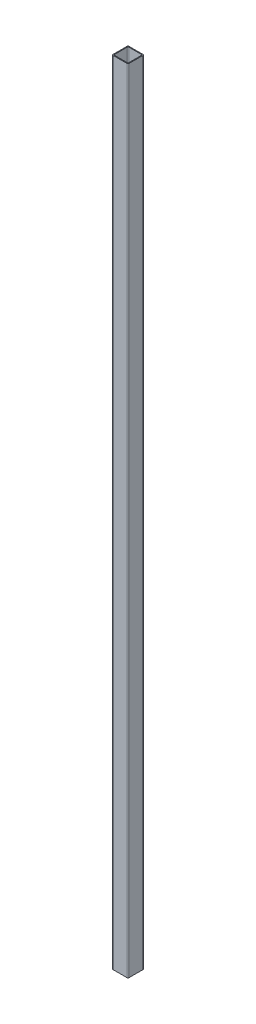
SolidWorks part; units mm, degrees
ref_plane "Спереди" through (0, 0, 0) normal (0, 0, 1) x (1, 0, 0)
ref_plane "Сверху" through (0, 0, 0) normal (0, 1, 0) x (1, 0, 0)
ref_plane "Справа" through (0, 0, 0) normal (1, 0, 0) x (0, 0, -1)
sketch "Эскиз2" plane through (0, 0, 0) normal (0, 1, 0) x (1, 0, 0)
  line L1 (-18, 20) -> (18, 20)
  line L2 (-20, 18) -> (-20, -18)
  line L3 (-18, -20) -> (18, -20)
  line L4 (20, 18) -> (20, -18)
  line L5 (-20, 20) -> (20, -20) construction
  line L6 (-20, -20) -> (20, 20) construction
  line L7 (16, -18) -> (-16, -18)
  line L8 (18, -16) -> (18, 16)
  line L9 (16, 18) -> (-16, 18)
  line L10 (-18, -16) -> (-18, 16)
  line L11 (18, -18) -> (-18, 18) construction
  line L12 (18, 18) -> (-18, -18) construction
  arc A0 (16, -18) -> (18, -16) centre (16, -16) ccw
  arc A1 (18, -20) -> (20, -18) centre (18, -18) ccw
  arc A2 (-20, -18) -> (-18, -20) centre (-18, -18) ccw
  arc A3 (-16, -18) -> (-18, -16) centre (-16, -16) cw
  arc A4 (18, 20) -> (20, 18) centre (18, 18) cw
  arc A5 (18, 16) -> (16, 18) centre (16, 16) ccw
  arc A6 (-18, 20) -> (-20, 18) centre (-18, 18) ccw
  arc A7 (-16, 18) -> (-18, 16) centre (-16, 16) ccw
  point P0 (0, 0)
  point P6 (0, 0)
  dimension "D5" = 2
  dimension "D1" = 40
  dimension "D2" = 40
  dimension "D3" = 2
  dimension "D4" = 2
extrude "Бобышка-Вытянуть1" add sketch "Эскиз2" along normal blind 2000
